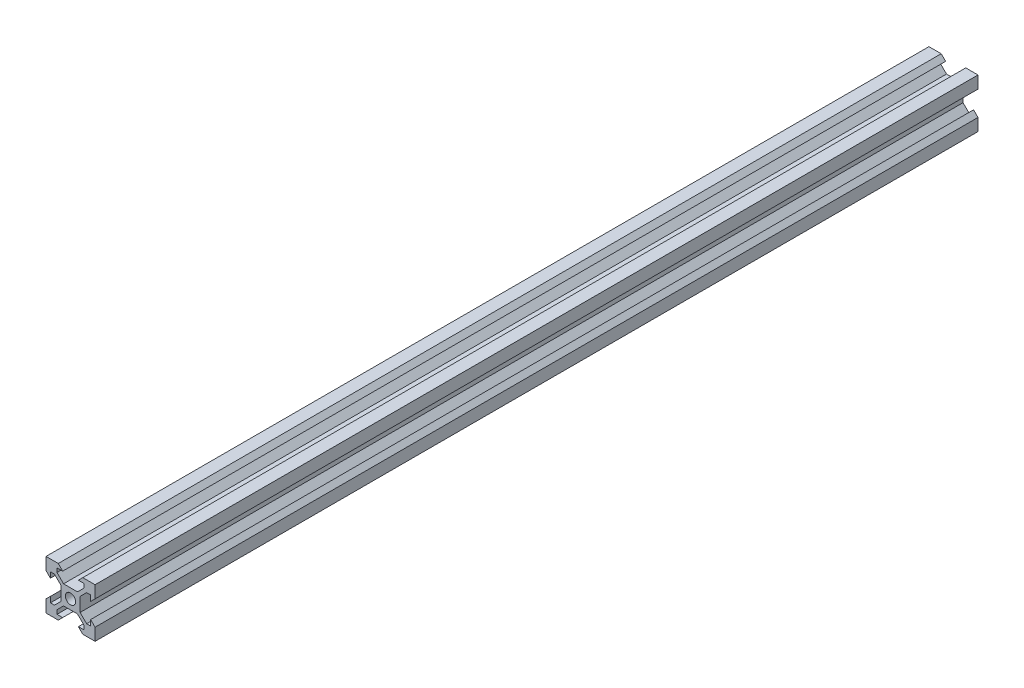
SolidWorks part; units mm, degrees
ref_plane "Front Plane" through (0, 0, 0) normal (0, 0, 1) x (1, 0, 0)
ref_plane "Top Plane" through (0, 0, 0) normal (0, 1, 0) x (1, 0, 0)
ref_plane "Right Plane" through (0, 0, 0) normal (1, 0, 0) x (0, 0, -1)
sketch "Sketch1" plane through (0, 0, 0) normal (0, 0, 1) x (1, 0, 0)
  line L0 (-10, 10) -> (-10, 5)
  line L1 (-10, 5) -> (-8.2, 3.2)
  line L2 (-8.2, 3.2) -> (-8.2, 5.4993)
  line L3 (-8.2, 5.4993) -> (-6.56, 5.4993)
  line L4 (-6.56, 5.4993) -> (-3.9007, 2.84)
  line L5 (-3.9007, 2.84) -> (-3.9007, -2.84)
  line L6 (-3.9007, -2.84) -> (-6.56, -5.4993)
  line L7 (-6.56, -5.4993) -> (-8.2, -5.4993)
  line L8 (-8.2, -5.4993) -> (-8.2, -3.2)
  line L9 (-8.2, -3.2) -> (-10, -5)
  line L10 (-10, -5) -> (-10, -10)
  line L11 (-10, -10) -> (-5, -10)
  line L12 (-5, -10) -> (-3.2, -8.2)
  line L13 (-3.2, -8.2) -> (-5.4993, -8.2)
  line L14 (-5.4993, -8.2) -> (-5.4993, -6.56)
  line L15 (-5.4993, -6.56) -> (-2.84, -3.9007)
  line L16 (-2.84, -3.9007) -> (2.84, -3.9007)
  line L17 (2.84, -3.9007) -> (5.4993, -6.56)
  line L18 (5.4993, -6.56) -> (5.4993, -8.2)
  line L19 (5.4993, -8.2) -> (3.2, -8.2)
  line L20 (3.2, -8.2) -> (5, -10)
  line L21 (5, -10) -> (10, -10)
  line L22 (10, -10) -> (10, -5)
  line L23 (10, -5) -> (8.2, -3.2)
  line L24 (8.2, -3.2) -> (8.2, -5.4993)
  line L25 (8.2, -5.4993) -> (6.56, -5.4993)
  line L26 (6.56, -5.4993) -> (3.9007, -2.84)
  line L27 (3.9007, -2.84) -> (3.9007, 2.84)
  line L28 (3.9007, 2.84) -> (6.56, 5.4993)
  line L29 (6.56, 5.4993) -> (8.2, 5.4993)
  line L30 (8.2, 5.4993) -> (8.2, 3.2)
  line L31 (8.2, 3.2) -> (10, 5)
  line L32 (10, 5) -> (10, 10)
  line L33 (10, 10) -> (5, 10)
  line L34 (5, 10) -> (3.2, 8.2)
  line L35 (3.2, 8.2) -> (5.4993, 8.2)
  line L36 (5.4993, 8.2) -> (5.4993, 6.56)
  line L37 (5.4993, 6.56) -> (2.84, 3.9007)
  line L38 (2.84, 3.9007) -> (-2.84, 3.9007)
  line L39 (-2.84, 3.9007) -> (-5.4993, 6.56)
  line L40 (-5.4993, 6.56) -> (-5.4993, 8.2)
  line L41 (-5.4993, 8.2) -> (-3.2, 8.2)
  line L42 (-3.2, 8.2) -> (-5, 10)
  line L43 (-5, 10) -> (-10, 10)
  circle A0 centre (0, 0) radius 2.1
extrude "Boss-Extrude1" add sketch "Sketch1" against normal blind 360
ref_plane "基准面1" through (0, 0, 0) normal (0, 0, 1) x (1, 0, 0)
